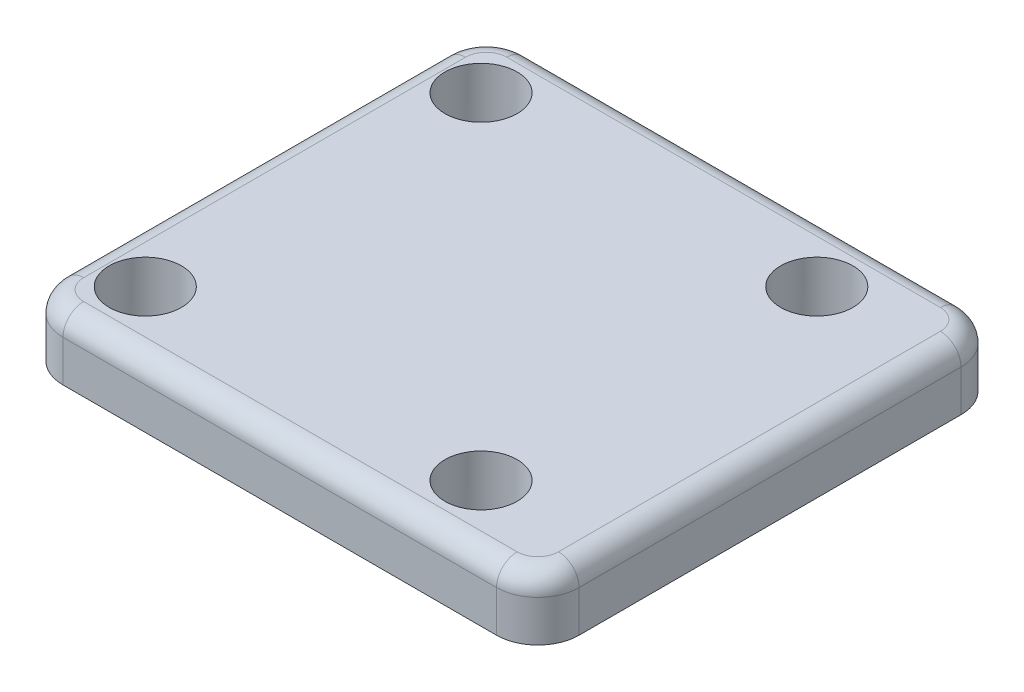
SolidWorks part; units mm, degrees
ref_plane "Front Plane" through (0, 0, 0) normal (0, 0, 1) x (1, 0, 0)
ref_plane "Top Plane" through (0, 0, 0) normal (0, 1, 0) x (1, 0, 0)
ref_plane "Right Plane" through (0, 0, 0) normal (1, 0, 0) x (0, 0, -1)
sketch "Sketch1" plane through (0, 0, 0) normal (0, 1, 0) x (1, 0, 0)
  line L1 (-18, 22.5) -> (24, 22.5)
  line L2 (-22, 18.5) -> (-22, -18.5)
  line L3 (-18, -22.5) -> (24, -22.5)
  line L4 (28, 18.5) -> (28, -18.5)
  arc A0 (24, 22.5) -> (28, 18.5) centre (24, 18.5) cw
  arc A1 (24, -22.5) -> (28, -18.5) centre (24, -18.5) ccw
  arc A2 (-22, -18.5) -> (-18, -22.5) centre (-18, -18.5) ccw
  arc A3 (-22, 18.5) -> (-18, 22.5) centre (-18, 18.5) cw
  point P7 (28, 22.5)
  point P10 (28, -22.5)
  point P15 (-22, 22.5)
  dimension "D5" = 4
  dimension "D1" = 50
  dimension "D2" = 45
  dimension "D3" = 22.5
  dimension "D4" = 22
extrude "Boss-Extrude1" add sketch "Sketch1" along normal blind 6
fillet "Fillet1" radius 2 8 edges at (-20.8284, 6, -21.3284) (3, 6, -22.5) (26.8284, 6, -21.3284) (28, 6, 0) (26.8284, 6, 21.3284) (3, 6, 22.5) (-20.8284, 6, 21.3284) (-22, 6, 0)
sketch "Sketch2" plane through (0, 0, 0) normal (0, -1, 0) x (1, 0, 0)
  circle A0 centre (0, 0) radius 16
  dimension "D1" = 32
extrude "Boss-Extrude2" add sketch "Sketch2" along normal blind 2
chamfer "Chamfer1" distance 1 angle 45 1 edges at (0, -2, -16)
sketch "Sketch3" plane through (0, 6, 0) normal (0, 1, 0) x (1, 0, 0)
  line L0 (0, 0) -> (-23, 0) construction
  line L1 (-23, 0) -> (0, 0) construction
  line L2 (0, 0) -> (-16.2635, 16.2635) construction
  circle A0 centre (0, 0) radius 23 construction
  circle A1 centre (-16.2635, 16.2635) radius 3.5
  circle A2 centre (16.2635, 16.2635) radius 3.5
  circle A3 centre (16.2635, -16.2635) radius 3.5
  circle A4 centre (-16.2635, -16.2635) radius 3.5
  point P15 (0, 0)
  dimension "D1" = 46
  dimension "D3" = 7
  dimension "D2" = 45
  dimension "D4" = 4
extrude "Cut-Extrude1" cut sketch "Sketch3" against normal through all
